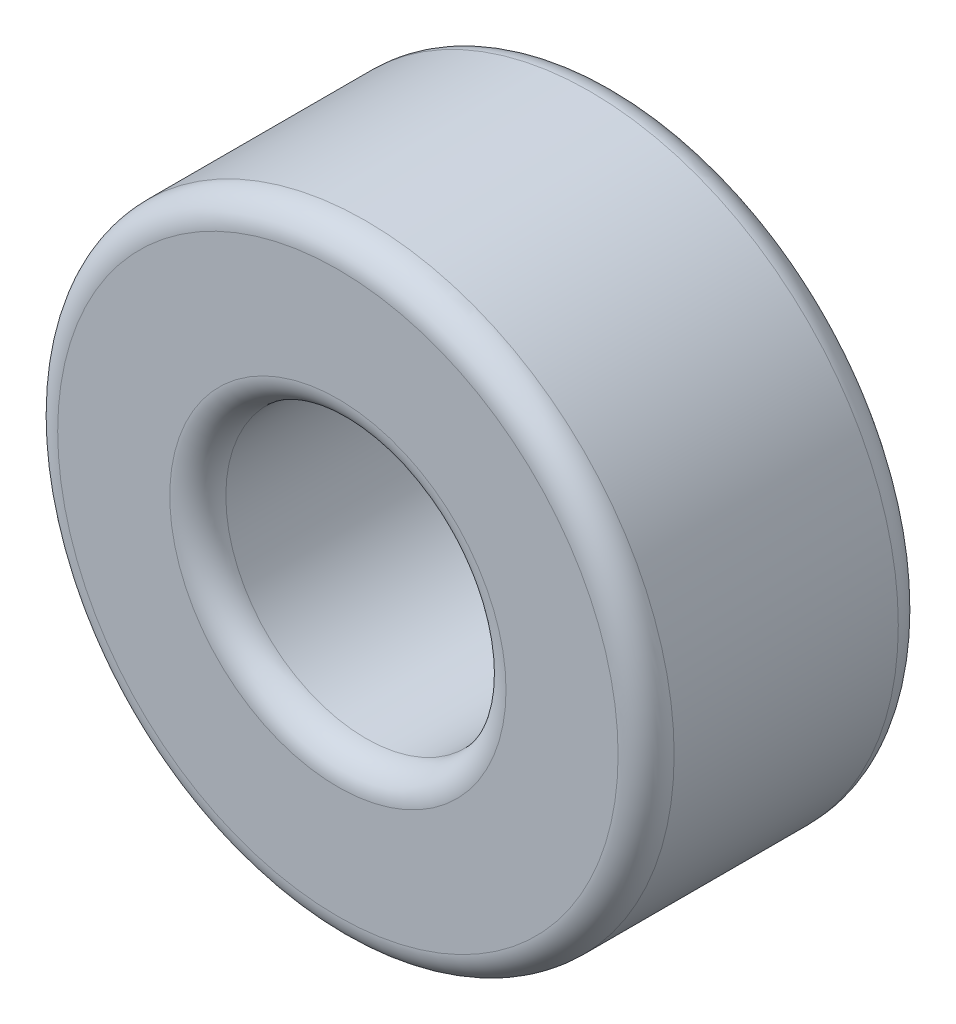
SolidWorks part; units mm, degrees
ref_plane "前视基准面" through (0, 0, 0) normal (0, 0, 1) x (1, 0, 0)
ref_plane "上视基准面" through (0, 0, 0) normal (0, 1, 0) x (1, 0, 0)
ref_plane "右视基准面" through (0, 0, 0) normal (1, 0, 0) x (0, 0, -1)
sketch "草图1" plane through (0, 0, 0) normal (0, 0, 1) x (1, 0, 0)
  circle A0 centre (0, 0) radius 5.5
  circle A1 centre (0, 0) radius 2.5
  dimension "D1" = 11
  dimension "D2" = 5
extrude "凸台-拉伸1" add sketch "草图1" along normal blind 5
fillet "圆角1" radius 0.5 4 edges at (2.5, 0, 0) (5.5, 0, 0) (2.5, 0, 5) (5.5, 0, 5)
